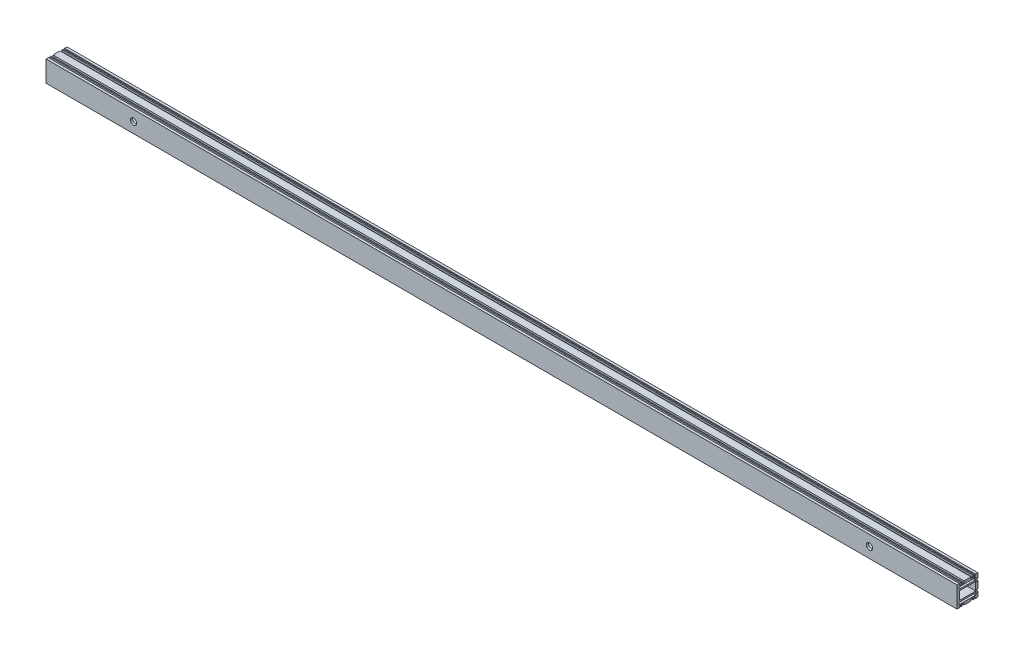
SolidWorks part; units mm, degrees
ref_plane "前视基准面" through (0, 0, 0) normal (0, 0, 1) x (1, 0, 0)
ref_plane "上视基准面" through (0, 0, 0) normal (0, 1, 0) x (1, 0, 0)
ref_plane "右视基准面" through (0, 0, 0) normal (1, 0, 0) x (0, 0, -1)
sketch "草图1" plane through (0, 0, 0) normal (1, 0, 0) x (0, 0, -1)
  line L0 (-15, 15) -> (15, -15) construction
  line L1 (-15, 15) -> (-11.5, 15)
  line L2 (-15, 15) -> (-15, -15)
  line L3 (-15, -15) -> (-11.5, -15)
  line L4 (15, 15) -> (15, 8)
  line L5 (15, 15) -> (-15, -15) construction
  line L6 (-11.5, 15) -> (-11.5, 13.5)
  line L7 (-11.5, 13.5) -> (-11, 13.5)
  line L8 (-11, 13.5) -> (-11, 12)
  line L9 (-11, 12) -> (-9.5, 12)
  line L10 (-9.5, 12) -> (-9.5, 15)
  line L11 (-9.5, 15) -> (-8, 15)
  line L12 (-8, 15) -> (-8, 12.5)
  line L13 (-8, 12.5) -> (-5, 12.5)
  line L14 (-5, 12.5) -> (-5, 15)
  line L15 (-5, 15) -> (5, 15)
  line L16 (0, 21.5201) -> (0, -18.309) construction
  line L17 (0, 55) -> (0, -55) construction
  line L18 (5, 12.5) -> (5, 15)
  line L19 (8, 12.5) -> (5, 12.5)
  line L20 (8, 15) -> (8, 12.5)
  line L21 (9.5, 15) -> (8, 15)
  line L22 (9.5, 12) -> (9.5, 15)
  line L23 (11, 12) -> (9.5, 12)
  line L24 (11, 13.5) -> (11, 12)
  line L25 (11.5, 13.5) -> (11, 13.5)
  line L26 (11.5, 15) -> (11.5, 13.5)
  line L27 (8, 15) -> (9.5, 15)
  line L28 (11.5, 15) -> (15, 15)
  line L29 (-19.8303, 0) -> (22.13, 0) construction
  line L30 (55, 0) -> (-55, 0) construction
  line L31 (8, -15) -> (9.5, -15)
  line L32 (11.5, -15) -> (11.5, -13.5)
  line L33 (11.5, -13.5) -> (11, -13.5)
  line L34 (11, -13.5) -> (11, -12)
  line L35 (11, -12) -> (9.5, -12)
  line L36 (9.5, -12) -> (9.5, -15)
  line L37 (9.5, -15) -> (8, -15)
  line L38 (8, -15) -> (8, -12.5)
  line L39 (8, -12.5) -> (5, -12.5)
  line L40 (5, -12.5) -> (5, -15)
  line L41 (-5, -15) -> (5, -15)
  line L42 (-5, -12.5) -> (-5, -15)
  line L43 (-8, -12.5) -> (-5, -12.5)
  line L44 (-8, -15) -> (-8, -12.5)
  line L45 (-9.5, -15) -> (-8, -15)
  line L46 (-9.5, -12) -> (-9.5, -15)
  line L47 (-11, -12) -> (-9.5, -12)
  line L48 (-11, -13.5) -> (-11, -12)
  line L49 (-11.5, -13.5) -> (-11, -13.5)
  line L50 (-11.5, -15) -> (-11.5, -13.5)
  line L51 (-9.5, -15) -> (-8, -15)
  line L52 (-5, -15) -> (5, -15)
  line L53 (8, -15) -> (9.5, -15)
  line L54 (11.5, -15) -> (15, -15)
  line L55 (15, 8) -> (12.5, 8)
  line L56 (12.5, 8) -> (12.5, 5)
  line L57 (12.5, 5) -> (15, 5)
  line L58 (12.5, -5) -> (15, -5)
  line L59 (12.5, -8) -> (12.5, -5)
  line L60 (15, -8) -> (12.5, -8)
  line L61 (15, 5) -> (15, -5)
  line L62 (15, -8) -> (15, -15)
  line L63 (12, -10.5) -> (12, -8.5)
  line L64 (-11.5, 11) -> (11.5, 11)
  line L65 (-12, 10.5) -> (-12, 8.5)
  line L66 (-11.5, 8) -> (11.5, 8)
  line L67 (12, 10.5) -> (12, 8.5)
  line L68 (-11.5, -8) -> (11.5, -8)
  line L69 (-12, -10.5) -> (-12, -8.5)
  line L70 (-11.5, -11) -> (11.5, -11)
  line L72 (-11.75, 6) -> (11.75, 6)
  line L73 (-11.75, 6) -> (-11.75, -6)
  line L74 (-11.75, -6) -> (11.75, -6)
  line L75 (11.75, 6) -> (11.75, -6)
  arc A0 (12, 8.5) -> (11.5, 8) centre (11.5, 8.5) cw
  arc A1 (11.5, 11) -> (12, 10.5) centre (11.5, 10.5) cw
  arc A2 (-11.5, 11) -> (-12, 10.5) centre (-11.5, 10.5) ccw
  arc A3 (-11.5, 8) -> (-12, 8.5) centre (-11.5, 8.5) cw
  arc A8 (-11.5, -8) -> (-12, -8.5) centre (-11.5, -8.5) ccw
  arc A9 (-11.5, -11) -> (-12, -10.5) centre (-11.5, -10.5) cw
  arc A10 (11.5, -11) -> (12, -10.5) centre (11.5, -10.5) ccw
  arc A11 (12, -8.5) -> (11.5, -8) centre (11.5, -8.5) ccw
  point P69 (12, 11)
  point P72 (-12, 11)
  point P77 (-11, -13.5)
  point P80 (11, -13.5)
  point P83 (11, 13.5)
  point P86 (-11, 13.5)
  point P99 (-12, -11)
  point P100 (12, -11)
  dimension "D17" = 0.5
  dimension "D1" = 3.5
  dimension "D2" = 1.5
  dimension "D3" = 0.5
  dimension "D4" = 1.5
  dimension "D5" = 3
  dimension "D6" = 30
  dimension "D7" = 30
  dimension "D8" = 1.5
  dimension "D9" = 2.5
  dimension "D10" = 3
  dimension "D11" = 2.5
  dimension "D12" = 7
  dimension "D13" = 3
  dimension "D14" = 4
  dimension "D15" = 3
  dimension "D16" = 24
  dimension "D19" = 23.5
  dimension "D20" = 12
extrude "凸台-拉伸1" add sketch "草图1" along normal mid plane 1301
hole_wizard "M6 螺纹孔1" positions "草图3" profile "草图2" tap size "M6" standard "GB"
sketch "草图3" plane through (0, 0, -15) normal (0, 0, -1) x (-1, 0, 0)
  line L0 (-650.5, -15) -> (650.5, -15) construction
  line L1 (-650.5, -8) -> (-650.5, -15) construction
  point P0 (630.5, 0)
  point P3 (615.5, 0)
  point P6 (-327.5, 0)
  point P9 (-342.5, 0)
  point P12 (-412.5, 0)
  point P15 (-427.5, 0)
  point P18 (-615.5, 0)
  point P21 (-630.5, 0)
  point P24 (-570.5, 0)
  point P26 (-472.5, 0)
  dimension "D1" = 15
  dimension "D2" = 80
  dimension "D3" = 178
sketch "草图2" plane through (-630.5, 0, -15) normal (1, 0, 0) x (0, 1, 0)
  line L0 (0, 0) -> (0, 20.5022)
  line L1 (0, 20.5022) -> (2.5, 19)
  line L2 (2.5, 19) -> (2.5, 0)
  line L5 (2.5, 0) -> (0, 0)
  line L10 (0, 20.5022) -> (-2.5, 19) construction
  line L11 (0, -6.35) -> (0, 107.95) construction
  dimension "螺纹孔钻头直径" = 5
  dimension "螺纹孔钻头深度" = 19
  dimension "导头角度" = 118
cosmetic thread "孔螺蚊线1" parameters "D1"=3.25, "D2"=6
cosmetic thread "孔螺蚊线2" parameters "D1"=3.25, "D2"=6
cosmetic thread "孔螺蚊线3" parameters "D1"=3.25, "D2"=6
cosmetic thread "孔螺蚊线4" parameters "D1"=3.25, "D2"=6
cosmetic thread "孔螺蚊线7" parameters "D1"=3.25, "D2"=6
cosmetic thread "孔螺蚊线8" parameters "D1"=3.25, "D2"=6
cosmetic thread "孔螺蚊线13" parameters "D1"=3.25, "D2"=6
cosmetic thread "孔螺蚊线14" parameters "D1"=3.25, "D2"=6
cosmetic thread "孔螺蚊线15" parameters "D1"=3.25, "D2"=6
cosmetic thread "孔螺蚊线16" parameters "D1"=3.25, "D2"=6
hole_wizard "M6 螺纹孔2" positions "草图5" profile "草图4" tap size "M6" standard "GB"
sketch "草图5" plane through (0, -15, 0) normal (0, -1, 0) x (-1, 0, 0)
  line L0 (-650.5, 15) -> (650.5, 15) construction
  line L1 (-650.5, 11.5) -> (-650.5, 15) construction
  line L2 (-650.5, -5) -> (-650.5, 5) construction
  line L3 (650.5, 11.5) -> (650.5, 15) construction
  point P0 (-630.5, 0)
  point P3 (-615.5, 0)
  point P6 (615.5, 0)
  point P9 (630.5, 0)
  point P12 (-137.5, 0)
  point P14 (-83.5, 0)
  point P16 (157.5, 0)
  point P18 (211.5, 0)
  dimension "D1" = 15
  dimension "D2" = 15
  dimension "D3" = 567
  dimension "D4" = 513
  dimension "D5" = 15
  dimension "D6" = 15
  dimension "D7" = 493
  dimension "D8" = 439
sketch "草图4" plane through (630.5, -15, 0) normal (1, 0, 0) x (0, 0, -1)
  line L0 (0, 0) -> (0, 20.5022)
  line L1 (0, 20.5022) -> (2.5, 19)
  line L2 (2.5, 19) -> (2.5, 0)
  line L5 (2.5, 0) -> (0, 0)
  line L10 (0, 20.5022) -> (-2.5, 19) construction
  line L11 (0, -6.35) -> (0, 107.95) construction
  dimension "螺纹孔钻头直径" = 5
  dimension "螺纹孔钻头深度" = 19
  dimension "导头角度" = 118
cosmetic thread "孔螺蚊线9" parameters "D1"=9, "D2"=6
cosmetic thread "孔螺蚊线10" parameters "D1"=9, "D2"=6
cosmetic thread "孔螺蚊线11" parameters "D1"=9, "D2"=6
cosmetic thread "孔螺蚊线12" parameters "D1"=9, "D2"=6
cosmetic thread "孔螺蚊线17" parameters "D1"=9, "D2"=6
cosmetic thread "孔螺蚊线18" parameters "D1"=9, "D2"=6
cosmetic thread "孔螺蚊线19" parameters "D1"=9, "D2"=6
cosmetic thread "孔螺蚊线20" parameters "D1"=9, "D2"=6
hole_wizard "Ø9.0 (9) 直径孔1" positions "草图7" profile "草图6" hole size "Ø9.0" standard "GB" end condition through all
sketch "草图7" plane through (0, 0, 15) normal (0, 0, 1) x (1, 0, 0)
  line L0 (650.5, -15) -> (-650.5, -15) construction
  line L1 (-650.5, 15) -> (-650.5, -15) construction
  line L2 (650.5, 15) -> (650.5, -15) construction
  point P0 (525.5, 0)
  point P2 (-525.5, 0)
  dimension "D1" = 15
  dimension "D2" = 125
  dimension "D3" = 15
  dimension "D4" = 125
sketch "草图6" plane through (525.5, 0, 15) normal (1, 0, 0) x (0, -1, 0)
  line L0 (0, 0) -> (0, 30)
  line L1 (0, 30) -> (4.5, 30)
  line L2 (4.5, 30) -> (4.5, 0)
  line L5 (4.5, 0) -> (0, 0)
  line L11 (0, -6.35) -> (0, 107.95) construction
  dimension "通孔孔直径" = 9
  dimension "通孔孔深度" = 30
hole_wizard "Ø7.0 (7) 直径孔1" positions "草图9" profile "草图8" hole size "Ø7.0" standard "GB"
sketch "草图9" plane through (0, 0, -15) normal (0, 0, -1) x (-1, 0, 0)
  line L0 (-650.5, -15) -> (650.5, -15) construction
  line L1 (650.5, -8) -> (650.5, -15) construction
  point P0 (-111, 0)
  point P2 (399, 0)
  dimension "D1" = 15
  dimension "D2" = 251.5
  dimension "D3" = 761.5
  dimension "D4" = 15
sketch "草图8" plane through (111, 0, -15) normal (1, 0, 0) x (0, 1, 0)
  line L0 (0, 0) -> (0, 17.103)
  line L1 (0, 17.103) -> (3.5, 15)
  line L2 (3.5, 15) -> (3.5, 0)
  line L5 (3.5, 0) -> (0, 0)
  line L10 (0, 17.103) -> (-3.5, 15) construction
  line L11 (0, -6.35) -> (0, 107.95) construction
  dimension "孔直径" = 7
  dimension "孔深度" = 15
  dimension "导头角度" = 118
hole_wizard "M4 螺纹孔1" positions "草图11" profile "草图10" tap size "M4" standard "GB"
sketch "草图11" plane through (0, -15, 0) normal (0, -1, 0) x (-1, 0, 0)
  line L0 (-650.5, 15) -> (650.5, 15) construction
  line L1 (-650.5, 11.5) -> (-650.5, 15) construction
  point P0 (-540.5, 0)
  point P2 (-280.5, 0)
  dimension "D1" = 15
  dimension "D2" = 15
  dimension "D3" = 110
  dimension "D4" = 370
sketch "草图10" plane through (540.5, -15, 0) normal (1, 0, 0) x (0, 0, -1)
  line L0 (0, 0) -> (0, 12.4914)
  line L1 (0, 12.4914) -> (1.65, 11.5)
  line L2 (1.65, 11.5) -> (1.65, 0)
  line L5 (1.65, 0) -> (0, 0)
  line L10 (0, 12.4914) -> (-1.65, 11.5) construction
  line L11 (0, -6.35) -> (0, 107.95) construction
  dimension "螺纹孔钻头直径" = 3.3
  dimension "螺纹孔钻头深度" = 11.5
  dimension "导头角度" = 118
cosmetic thread "孔螺蚊线21" parameters "D1"=8, "D2"=4
cosmetic thread "孔螺蚊线22" parameters "D1"=8, "D2"=4
